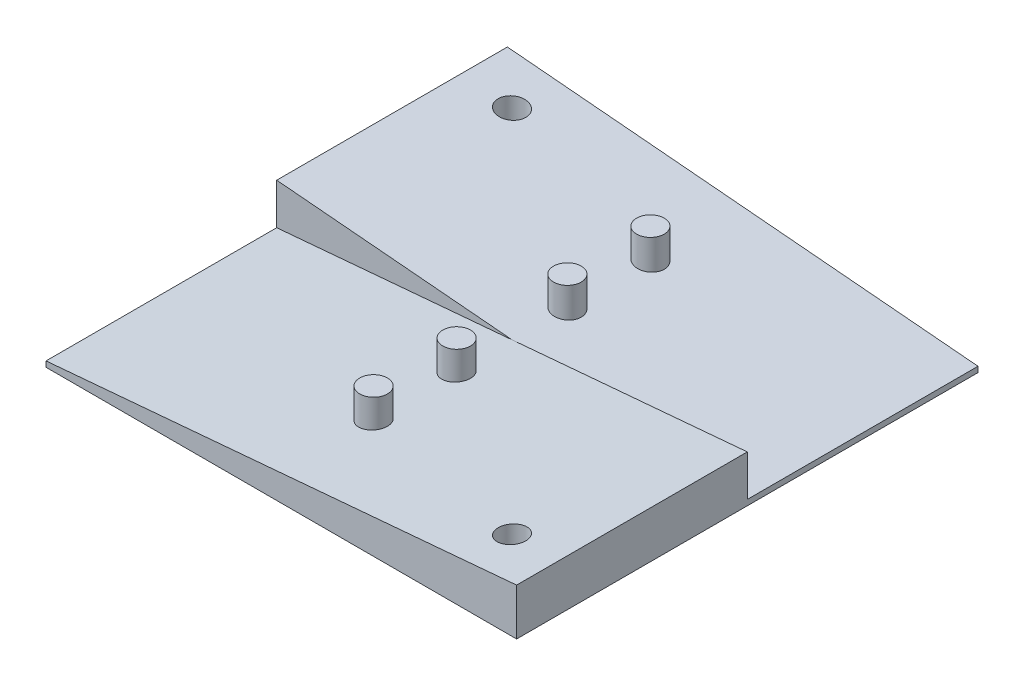
SolidWorks part; units mm, degrees
material "ABS"
ref_plane "Plano frontal" through (0, 0, 0) normal (0, 0, 1) x (1, 0, 0)
ref_plane "Plano superior" through (0, 0, 0) normal (0, 1, 0) x (1, 0, 0)
ref_plane "Plano direito" through (0, 0, 0) normal (1, 0, 0) x (0, 0, -1)
sketch "Esboço2" plane through (0, 0, 0) normal (0, 1, 0) x (1, 0, 0)
  line L7 (25.5, 25) -> (-25.5, 25)
  line L8 (25.5, 25) -> (25.5, -25)
  line L9 (25.5, -25) -> (-25.5, -25)
  line L10 (-25.5, 25) -> (-25.5, -25)
  line L11 (25.5, 25) -> (-25.5, -25) construction
  line L12 (25.5, -25) -> (-25.5, 25) construction
  point P0 (0, 0)
  dimension "D1" = 50
  dimension "D2" = 51
extrude "Ressalto-extrusão2" add sketch "Esboço2" along normal blind 6
sketch "Esboço3" plane through (0, 0, 25) normal (0, 0, 1) x (1, 0, 0)
  line L0 (-25.5, 0.6) -> (25.5, 5.0619)
  line L1 (25.5, 6) -> (25.5, 0) construction
  line L2 (-25.5, 6) -> (-25.5, 0) construction
  line L3 (-25.5, 0) -> (25.5, 0) construction
  line L4 (-25.5, 0.6) -> (-25.5, 6)
  line L5 (-25.5, 6) -> (25.5, 6)
  line L6 (25.5, 6) -> (25.5, 5.0619)
  dimension "D1" = 5
  dimension "D2" = 0.6
extrude "Corte-extrusão1" cut sketch "Esboço3" against normal blind 25
sketch "Esboço4" plane through (0, 0, -25) normal (0, 0, -1) x (-1, 0, 0)
  line L0 (-25.5, 0.6) -> (25.5, 5.0619)
  line L1 (-25.5, 6) -> (-25.5, 0) construction
  line L2 (25.5, 6) -> (25.5, 0) construction
  line L3 (-25.5, 0.6) -> (-25.5, 6)
  line L4 (-25.5, 6) -> (25.5, 6)
  line L5 (25.5, 6) -> (25.5, 5.0619)
  line L7 (-25.5, 0) -> (25.5, 0) construction
  dimension "D1" = 0.6
  dimension "D2" = 5
extrude "Corte-extrusão3" cut sketch "Esboço4" against normal blind 25
sketch "Esboço5" plane through (0, 0, 0) normal (0, -1, 0) x (1, 0, 0)
  line L0 (0, 6) -> (0, -6) construction
  circle A0 centre (0, 6) radius 1.5
  circle A1 centre (0, 15) radius 1.5
  circle A2 centre (0, -15) radius 1.5
  circle A3 centre (0, -6) radius 1.5
  point P12 (0, 0)
  dimension "D1" = 3
  dimension "D2" = 3
  dimension "D3" = 15
  dimension "D4" = 6
  dimension "D5" = 15
extrude "Ressalto-extrusão3" add sketch "Esboço5" against normal blind 6
sketch "Esboço8" plane through (0, 0, 0) normal (0, -1, 0) x (1, 0, 0)
  line L1 (20, 20) -> (-20, 20) construction
  line L2 (20, 20) -> (20, -20) construction
  line L3 (20, -20) -> (-20, -20) construction
  line L4 (-20, 20) -> (-20, -20) construction
  line L5 (20, 20) -> (-20, -20) construction
  line L6 (20, -20) -> (-20, 20) construction
  circle A1 centre (20, 20) radius 1.5
  circle A3 centre (-20, -20) radius 1.5
  point P8 (0, 0)
  point P9 (0, 0)
  point P14 (0, 0)
  point P15 (0, 0)
  point P16 (0, 0)
  dimension "D1" = 3
  dimension "D3" = 3
  dimension "D2" = 40
extrude "Corte-extrusão6" cut sketch "Esboço8" against normal through all
chamfer "Chanfro2" distance 1.5 angle 45 2 edges at (-20, 0, -21.5) (20, 0, 18.5)
equation "\"D5@Esboço5\"=\"D3@Esboço5\""
